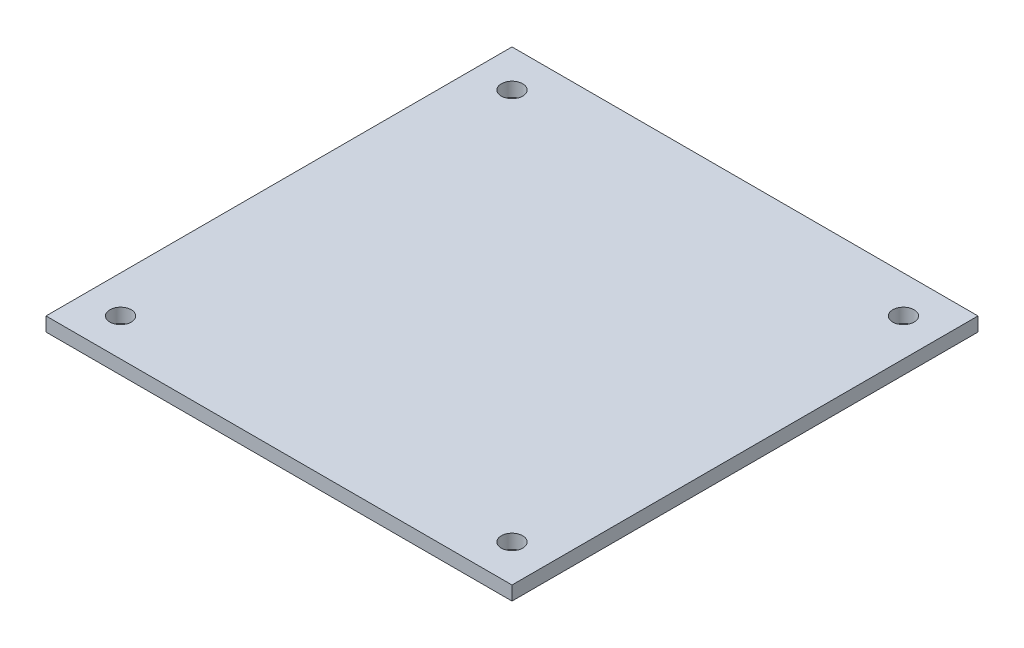
SolidWorks part; units mm, degrees
ref_plane "Plan de face" through (0, 0, 0) normal (0, 0, 1) x (1, 0, 0)
ref_plane "Plan de dessus" through (0, 0, 0) normal (0, 1, 0) x (1, 0, 0)
ref_plane "Plan de droite" through (0, 0, 0) normal (1, 0, 0) x (0, 0, -1)
sketch "Esquisse1" plane through (0, 0, 0) normal (0, 1, 0) x (1, 0, 0)
  line L1 (-49.8904, 45.5515) -> (0.1096, 45.5515)
  line L2 (-49.8904, 45.5515) -> (-49.8904, -4.4485)
  line L3 (-49.8904, -4.4485) -> (0.1096, -4.4485)
  line L4 (0.1096, 45.5515) -> (0.1096, -4.4485)
extrude "Boss.-Extru.1" add sketch "Esquisse1" along normal blind 1.5 contours L2 L3 L4 L1
sketch "Esquisse2" plane through (0, 1.5, 0) normal (0, 1, 0) x (1, 0, 0)
  line L0 (-49.8904, -4.4485) -> (0.1096, -4.4485) construction
  line L1 (0.1096, 45.5515) -> (0.1096, -4.4485) construction
  line L2 (-49.8904, 45.5515) -> (-49.8904, -4.4485) construction
  line L3 (-49.8904, 45.5515) -> (0.1096, 45.5515) construction
  circle A0 centre (-3.8904, -0.4485) radius 1.15
  circle A1 centre (-45.8904, -0.4485) radius 1.15
  circle A2 centre (-45.8904, 41.5515) radius 1.15
  circle A3 centre (-3.8904, 41.5515) radius 1.15
  dimension "D1" = 4
  dimension "D3" = 4
  dimension "D5" = 4
  dimension "D7" = 4
  dimension "D2" = 4
  dimension "D4" = 4
  dimension "D6" = 4
  dimension "D8" = 4
extrude "Enlèv. mat.-Extru.1" cut sketch "Esquisse2" against normal blind 1.5
